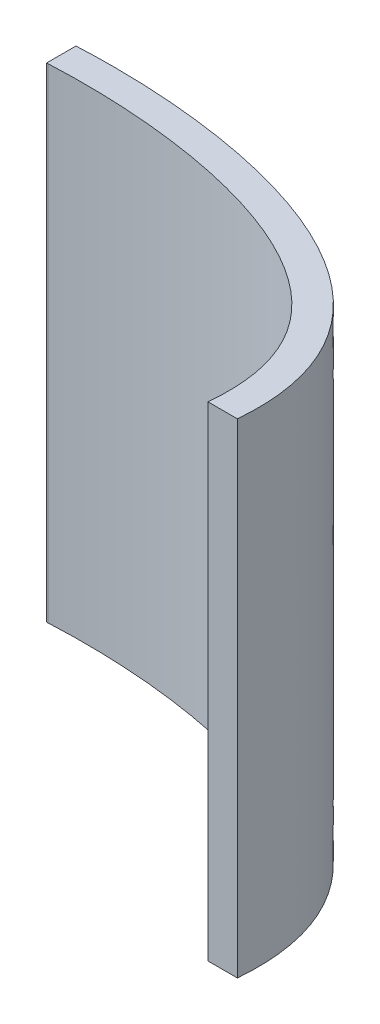
SolidWorks part; units mm, degrees
ref_plane "Front Plane" through (0, 0, 0) normal (0, 0, 1) x (1, 0, 0)
ref_plane "Top Plane" through (0, 0, 0) normal (0, 1, 0) x (1, 0, 0)
ref_plane "Right Plane" through (0, 0, 0) normal (1, 0, 0) x (0, 0, -1)
sketch "Sketch1" plane through (0, 0, 0) normal (0, 1, 0) x (1, 0, 0)
  line L0 (128.5797, 131.404) -> (183.5797, 131.404) construction
  line L1 (183.5797, 131.404) -> (183.5797, 98.404) construction
  line L2 (183.5797, 98.404) -> (179.5797, 98.404) construction
  line L3 (179.5946, 98.7488) -> (179.5797, 98.404)
  line L4 (179.5797, 98.404) -> (179.5797, 131.404) construction
  line L5 (128.5797, 131.404) -> (128.5797, 127.404) construction
  line L6 (179.5797, 98.404) -> (183.5797, 98.404)
  line L7 (128.5797, 127.404) -> (183.5797, 127.404) construction
  line L8 (128.5797, 131.404) -> (170.5248, 131.404) construction
  line L9 (138.5797, 131.404) -> (138.5797, 127.404) construction
  line L10 (183.5797, 114.904) -> (179.5797, 114.904) construction
  line L11 (179.5797, 114.904) -> (175.5797, 114.904) construction
  line L12 (175.5797, 127.404) -> (175.5797, 98.404) construction
  line L13 (128.7793, 127.409) -> (128.5797, 127.404)
  line L14 (128.5797, 127.404) -> (128.5797, 131.404)
  spline S0 degree 3 poles (128.5797, 131.404) (150.8179, 132.5153) (186.0021, 126.4038) (183.5797, 98.404) knots 0 0 0 0 1 1 1 1
  spline S1 degree 1 poles (128.7793, 127.409) (179.5946, 98.7488) knots 0 0 1 1 construction
  spline S2 degree 3 poles (128.7793, 127.409) (129.4569, 127.4428) (130.7965, 127.4951) (133.6089, 127.5442) (137.252, 127.4903) (141.7773, 127.2218) (147.898, 126.5656) (155.5164, 125.1405) (163.9599, 122.3416) (169.876, 119.0558) (173.6674, 115.8716) (176.0016, 113.208) (177.8049, 110.2482) (178.8528, 107.4847) (179.3966, 105.0482) (179.6472, 103.0967) (179.7149, 101.354) (179.6783, 99.894) (179.6273, 99.1268) (179.5946, 98.7488) knots 0 0 0 0 0.03125 0.0625 0.125 0.1875 0.25 0.375 0.5 0.625 0.6875 0.75 0.8125 0.875 0.90625 0.9375 0.96875 0.984375 1 1 1 1
  point P16 (128.5797, 129.404)
  dimension "D1" = 55
  dimension "D2" = 33
  dimension "D3" = 4
  dimension "D4" = 10
  dimension "D5" = 16.5
  dimension "D6" = 4
extrude "Boss-Extrude1" add sketch "Sketch1" along normal blind 66
